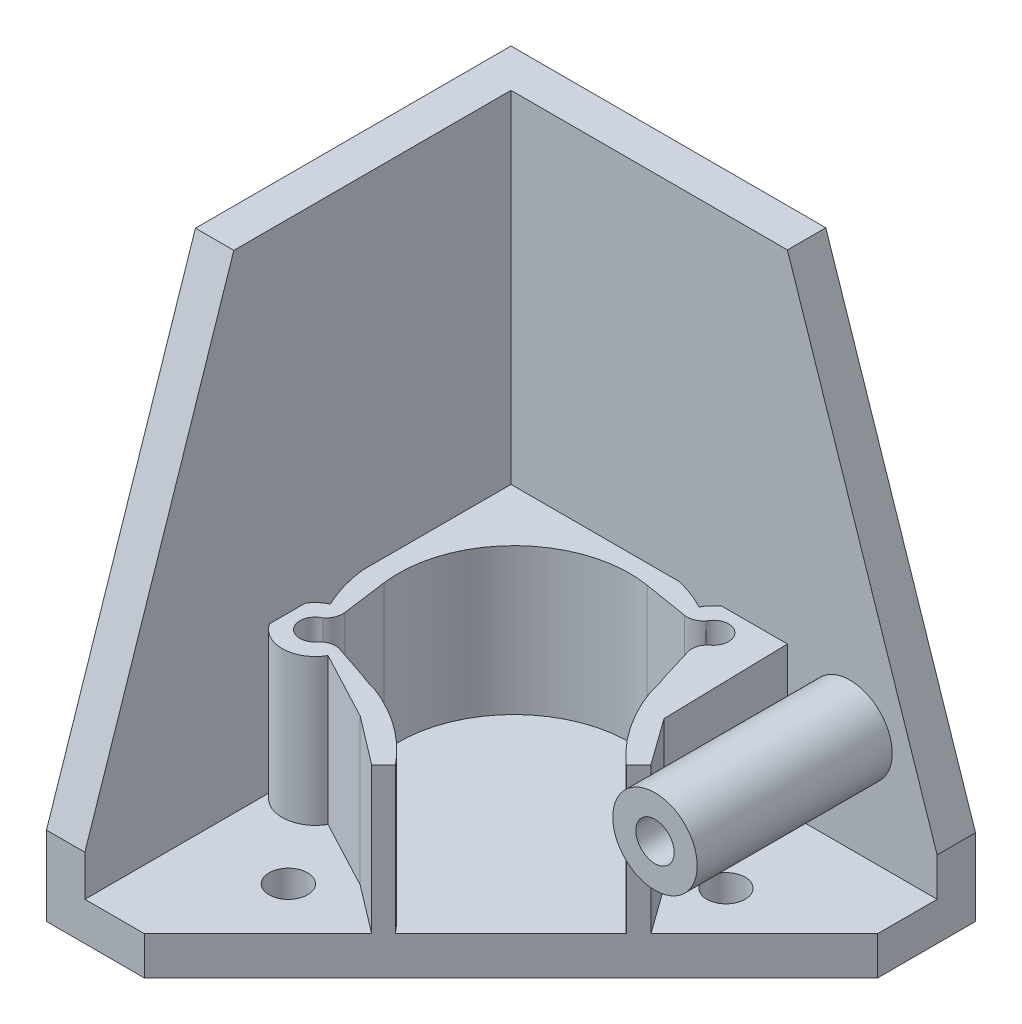
SolidWorks part; units mm, degrees
ref_plane "Front" through (0, 0, 0) normal (0, 0, 1) x (1, 0, 0)
ref_plane "Top" through (0, 0, 0) normal (0, 1, 0) x (1, 0, 0)
ref_plane "Right" through (0, 0, 0) normal (1, 0, 0) x (0, 0, -1)
sketch "Sketch1" plane through (0, 0, 0) normal (0, 1, 0) x (1, 0, 0)
  line L0 (0, 0) -> (0, 60.5)
  line L1 (0, -55) -> (0, 55) construction
  line L2 (0, 60.5) -> (60.5, 60.5)
  line L3 (60.5, 60.5) -> (60.5, 47.75)
  line L4 (60.5, 47.75) -> (12.75, 0)
  line L5 (-55, 0) -> (55, 0) construction
  line L6 (12.75, 0) -> (0, 0)
  dimension "D1" = 60.5
  dimension "D2" = 12.75
extrude "Boss-Extrude1" add sketch "Sketch1" along normal blind 5
sketch "Sketch4" plane through (0, 0, 0) normal (-1, 0, 0) x (0, 0, 1)
  line L0 (-60.5, 5) -> (-60.5, 68.5)
  line L1 (-60.5, 68.5) -> (-19.4, 68.5)
  line L2 (-19.4, 68.5) -> (0, 10.3086)
  line L3 (0, 10.3086) -> (0, 5)
  line L4 (0, -2.75) -> (0, 2.75) construction
  line L5 (-60.5, 5) -> (0, 5) construction
  line L6 (-60.5, 5) -> (0, 5)
  dimension "D1" = 63.5
  dimension "D2" = 41.1
  dimension "D3" = 61.34
extrude "Boss-Extrude2" add sketch "Sketch4" against normal blind 5
sketch "Sketch5" plane through (0, 0, -60.5) normal (0, 0, -1) x (-1, 0, 0)
  line L0 (0, 68.5) -> (-41, 68.5)
  line L1 (-41, 68.5) -> (-60.5, 10.0047)
  line L2 (-60.5, 10.0047) -> (-60.5, 5)
  line L6 (-60.5, 0) -> (0, 0)
  line L7 (0, 0) -> (0, 68.5)
  line L8 (0, 68.5) -> (-5, 68.5)
  line L9 (-5, 68.5) -> (-5, 5)
  line L10 (-5, 5) -> (-60.5, 5)
  line L11 (-60.5, 5) -> (-60.5, 0)
  line L12 (-60.5, 0) -> (0, 0)
  line L13 (0, 0) -> (0, 68.5)
  line L14 (0, 68.5) -> (-5, 68.5)
  line L15 (-5, 68.5) -> (-5, 5)
  line L16 (-5, 5) -> (-60.5, 5)
  line L17 (-60.5, 5) -> (-60.5, 0)
  line M13 (-5, 68.5) -> (-5, 5)
  line M14 (-5, 5) -> (-60.5, 5)
  dimension "D2" = 41
  dimension "D3" = 61.66
  dimension "D1" = 0
extrude "Boss-Extrude3" add sketch "Sketch5" against normal blind 5 contours L1 L2 L0 M14 M13
sketch "Sketch6" plane through (0, 5, 0) normal (0, 1, 0) x (1, 0, 0)
  line L0 (60.5, 60.5) -> (0, 60.5) construction
  line L4 (0, 19.4) -> (0, 0)
  line L5 (60.5, 55.5) -> (5, 55.5)
  line L6 (5, 55.5) -> (5, 0)
  line L7 (5, 0) -> (12.75, 0)
  line L8 (12.75, 0) -> (60.5, 47.75)
  line L9 (60.5, 47.75) -> (60.5, 55.5)
  line L10 (60.5, 55.5) -> (5, 55.5)
  line L11 (5, 55.5) -> (5, 0)
  line L12 (5, 0) -> (12.75, 0)
  line L13 (12.75, 0) -> (60.5, 47.75)
  line L14 (60.5, 47.75) -> (60.5, 55.5)
  line L15 (0, 0) -> (5, 0)
  line L16 (5, 0) -> (5, 19.4)
  line L17 (5, 19.4) -> (0, 19.4)
  line L18 (0, 19.4) -> (0, 0)
  line L19 (0, 0) -> (5, 0)
  line L20 (5, 0) -> (5, 19.4)
  line L21 (5, 19.4) -> (0, 19.4)
  line L24 (0, 60.5) -> (0, 19.4)
  line L25 (0, 19.4) -> (5, 19.4)
  line L26 (5, 19.4) -> (5, 55.5)
  line L27 (5, 55.5) -> (41, 55.5)
  line L28 (41, 55.5) -> (41, 60.5)
  line L29 (41, 60.5) -> (0, 60.5)
  line L30 (0, 60.5) -> (0, 19.4)
  line L31 (0, 19.4) -> (5, 19.4)
  line L32 (5, 19.4) -> (5, 55.5)
  line L33 (5, 55.5) -> (41, 55.5)
  line L34 (41, 55.5) -> (41, 60.5)
  line L35 (41, 60.5) -> (0, 60.5)
  circle A0 centre (16.5, 15) radius 2.5
  circle A1 centre (45.5, 43) radius 2.5
  dimension "D1" = 5
  dimension "D2" = 5
  dimension "D3" = 0
  dimension "D4" = 15
  dimension "D6" = 16.5
  dimension "D7" = 15
  dimension "D9" = 17.5
  dimension "D5" = 0
  dimension "D8" = 0
extrude "Cut-Extrude1" cut sketch "Sketch6" against normal through all contours A0 | A1
sketch "Sketch7" plane through (0, 5, 0) normal (0, 1, 0) x (1, 0, 0)
  line L0 (12.75, 0) -> (60.5, 47.75) construction
  line L1 (0, -33.275) -> (0, 33.275) construction
  line L2 (22.75, 38.1428) -> (36.625, 23.875) construction
  line L3 (27.5503, 14.8003) -> (21.3192, 19.5434)
  line L4 (21.3192, 19.5434) -> (12.3846, 24.2829)
  line L5 (36.625, 23.875) -> (9.463, 51.8061) construction
  line L6 (45.9495, 32.6929) -> (41.3821, 39.0539)
  line L7 (41.3821, 39.0539) -> (36.8938, 48.1173)
  line L8 (12.75, 0) -> (60.5, 47.75)
  line L9 (7.8273, 36.1137) -> (8.6247, 30.2498)
  line L10 (16.8588, 24.2829) -> (12.3846, 25.7746)
  line L11 (36.769, 43.6449) -> (35.4027, 48.1589)
  line L12 (25.1949, 53.0031) -> (31.0343, 52.0424)
  line L13 (41.3821, 39.0539) -> (41, 55.5)
  circle A0 centre (22.75, 38.1428) radius 15.06
  arc A1 (16.8588, 24.2829) -> (29.1015, 16.3515) centre (10.721, 1.3943) cw
  arc A2 (36.769, 43.6449) -> (44.3556, 31.1856) centre (59.82, 49.1414) ccw
  circle A3 centre (8.6247, 26.3793) radius 2
  circle A5 centre (34.9033, 51.9343) radius 2
  arc A6 (12.3846, 24.2829) -> (6.7403, 30.2498) centre (8.6247, 26.3793) cw
  arc A7 (6.7403, 30.2498) -> (31.0869, 53.926) centre (22.75, 38.1428) cw
  arc A8 (36.8938, 48.1173) -> (31.0869, 53.926) centre (34.9033, 51.9343) ccw
  arc A9 (8.6247, 30.2498) -> (7.8014, 28.2019) centre (6.4139, 29.9492) cw
  arc A10 (12.3846, 25.7746) -> (10.0999, 25.0288) centre (11.7459, 23.8589) ccw
  arc A11 (31.0343, 52.0424) -> (33.1043, 52.8082) centre (31.3965, 54.2439) ccw
  arc A12 (35.4027, 48.1589) -> (36.2121, 50.422) centre (37.3356, 48.7439) cw
  point P0 (22.75, 38.1428)
  line M5 (60.5, 55.5) -> (5, 55.5)
  line M6 (5, 55.5) -> (5, 0)
  line M8 (12.75, 0) -> (60.5, 47.75)
  dimension "D3" = 30.12
  dimension "D4" = 4
  dimension "D6" = 21.57
  dimension "D1" = 19.9
  dimension "D2" = 22.75
extrude "Boss-Extrude4" add sketch "Sketch7" along normal blind 19.05 contours L7 A8 A7 A6 L4 L3 A1 A0 A2 L6 A5 A3 M5 M6 M8 | A7 M6 M5 | A8 L7 L13 M5
sketch "Sketch9" plane through (0, 0, -55.5) normal (0, 0, 1) x (1, 0, 0)
  line L0 (41, 5) -> (60.5, 5) construction
  line L1 (41, 5) -> (60.5, 5)
  line L2 (44.1312, 24.05) -> (37.5012, 24.05) construction
  line L3 (44.1312, 24.05) -> (37.5012, 24.05)
  line L5 (0, 0) -> (60.5, 0)
  line L6 (0, 68.5) -> (0, 0)
  line L7 (41, 68.5) -> (0, 68.5)
  line L8 (60.5, 10.0047) -> (41, 68.5)
  line L9 (60.5, 0) -> (60.5, 10.0047)
  line L10 (0, 0) -> (60.5, 0)
  line L11 (0, 68.5) -> (0, 0)
  line L12 (41, 68.5) -> (0, 68.5)
  line L13 (60.5, 10.0047) -> (41, 68.5)
  line L14 (60.5, 0) -> (60.5, 10.0047)
  circle A0 centre (49.1523, 18.55) radius 5.5
  circle A1 centre (49.1523, 18.55) radius 2.5
  dimension "D2" = 5
  dimension "D3" = 3
  dimension "D1" = 0
extrude "Boss-Extrude5" add sketch "Sketch9" along normal blind 25.4
sketch "Sketch12" plane through (0, 0, -55.5) normal (0, 0, 1) x (1, 0, 0)
  line L11 (5, 24.05) -> (26.9142, 24.05)
  line L12 (26.9142, 24.05) -> (26.9142, 5)
  line L13 (26.9142, 5) -> (32.4913, 5)
  line L14 (32.4913, 5) -> (32.4913, 24.05)
  line L15 (32.4913, 24.05) -> (41, 24.05)
  line L16 (41, 24.05) -> (41, 5)
  line L17 (41, 5) -> (60.5, 5)
  line L18 (60.5, 5) -> (60.5, 10.0047)
  line L19 (60.5, 10.0047) -> (41, 68.5)
  line L20 (41, 68.5) -> (5, 68.5)
  line L21 (5, 68.5) -> (5, 24.05)
  line L22 (5, 24.05) -> (26.9142, 24.05)
  line L23 (26.9142, 24.05) -> (26.9142, 5)
  line L24 (26.9142, 5) -> (32.4913, 5)
  line L25 (32.4913, 5) -> (32.4913, 24.05)
  line L26 (32.4913, 24.05) -> (41, 24.05)
  line L27 (41, 24.05) -> (41, 5)
  line L28 (41, 5) -> (60.5, 5)
  line L29 (60.5, 5) -> (60.5, 10.0047)
  line L30 (60.5, 10.0047) -> (41, 68.5)
  line L31 (41, 68.5) -> (5, 68.5)
  line L32 (5, 68.5) -> (5, 24.05)
  circle A0 centre (49.1523, 18.55) radius 5.5 construction
  circle A1 centre (49.1523, 18.55) radius 5.5
  dimension "D1" = 0
